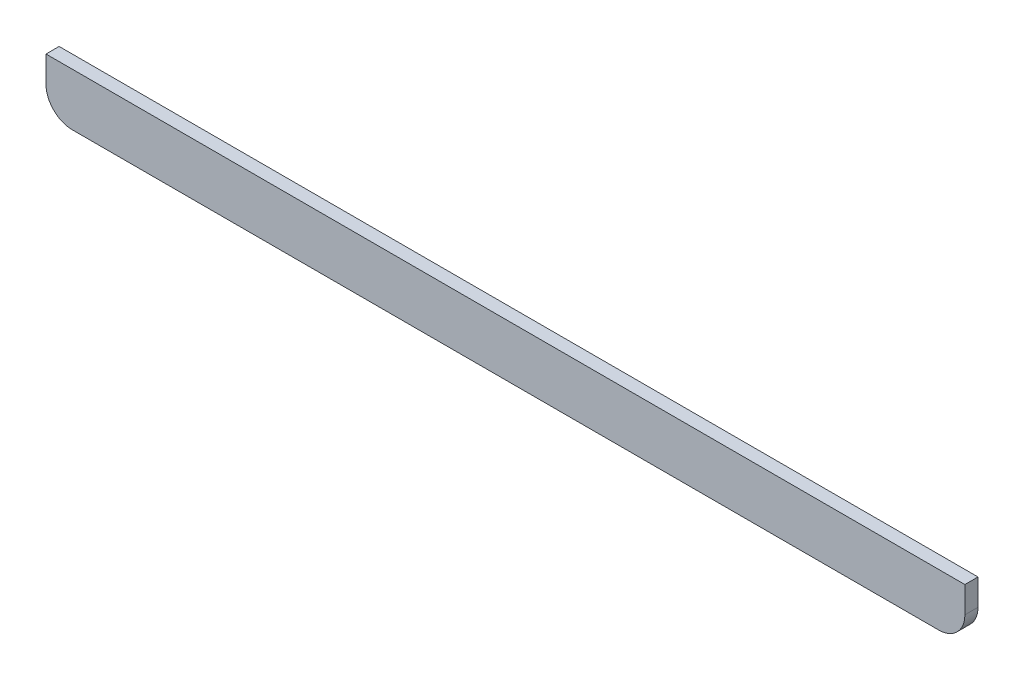
SolidWorks part; units mm, degrees
material "3.0205 (EN-AW 1200)"
ref_plane "Plan de face" through (0, 0, 0) normal (0, 0, 1) x (1, 0, 0)
ref_plane "Plan de dessus" through (0, 0, 0) normal (0, 1, 0) x (1, 0, 0)
ref_plane "Plan de droite" through (0, 0, 0) normal (1, 0, 0) x (0, 0, -1)
sketch "Esquisse1" plane through (0, 0, 0) normal (0, 0, 1) x (1, 0, 0)
  line L0 (0, 20) -> (10, 10) construction
  line L1 (10, 0) -> (340, 0)
  line L2 (0, 10) -> (0, 20)
  line L3 (0, 20) -> (350, 20)
  line L4 (350, 10) -> (350, 20)
  line L5 (10, 10) -> (340, 10) construction
  line L6 (340, 10) -> (350, 20) construction
  line L7 (350, 20) -> (340, 10) construction
  line L8 (340, 10) -> (340, 0) construction
  line L9 (10, 10) -> (10, 0) construction
  arc A0 (340, 0) -> (350, 10) centre (340, 10) ccw
  arc A1 (10, 0) -> (0, 10) centre (10, 10) cw
  point P9 (0, 0)
  dimension "D3" = 10
  dimension "D1" = 350
  dimension "D2" = 20
extrude "Boss.-Extru.1" add sketch "Esquisse1" along normal blind 5
